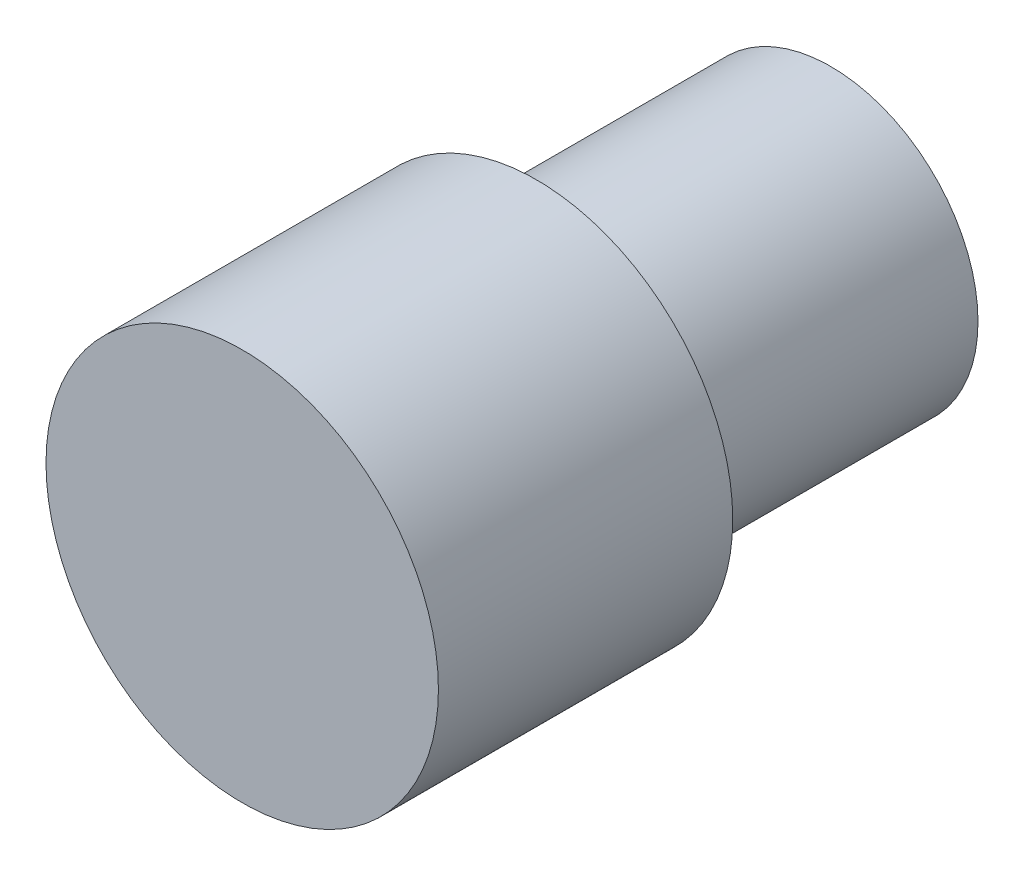
SolidWorks part; units mm, degrees
ref_plane "Front Plane" through (0, 0, 0) normal (0, 0, 1) x (1, 0, 0)
ref_plane "Top Plane" through (0, 0, 0) normal (0, 1, 0) x (1, 0, 0)
ref_plane "Right Plane" through (0, 0, 0) normal (1, 0, 0) x (0, 0, -1)
sketch "Sketch1" plane through (0, 0, 0) normal (0, 0, 1) x (1, 0, 0)
  circle A0 centre (0, 0) radius 7.5
  dimension "D1" = 15
extrude "Boss-Extrude1" add sketch "Sketch1" along normal blind 15
sketch "Sketch3" plane through (0, 0, 15) normal (0, 0, 1) x (1, 0, 0)
  circle A0 centre (0, 0) radius 10
  dimension "D1" = 20
extrude "Boss-Extrude2" add sketch "Sketch3" along normal blind 15
